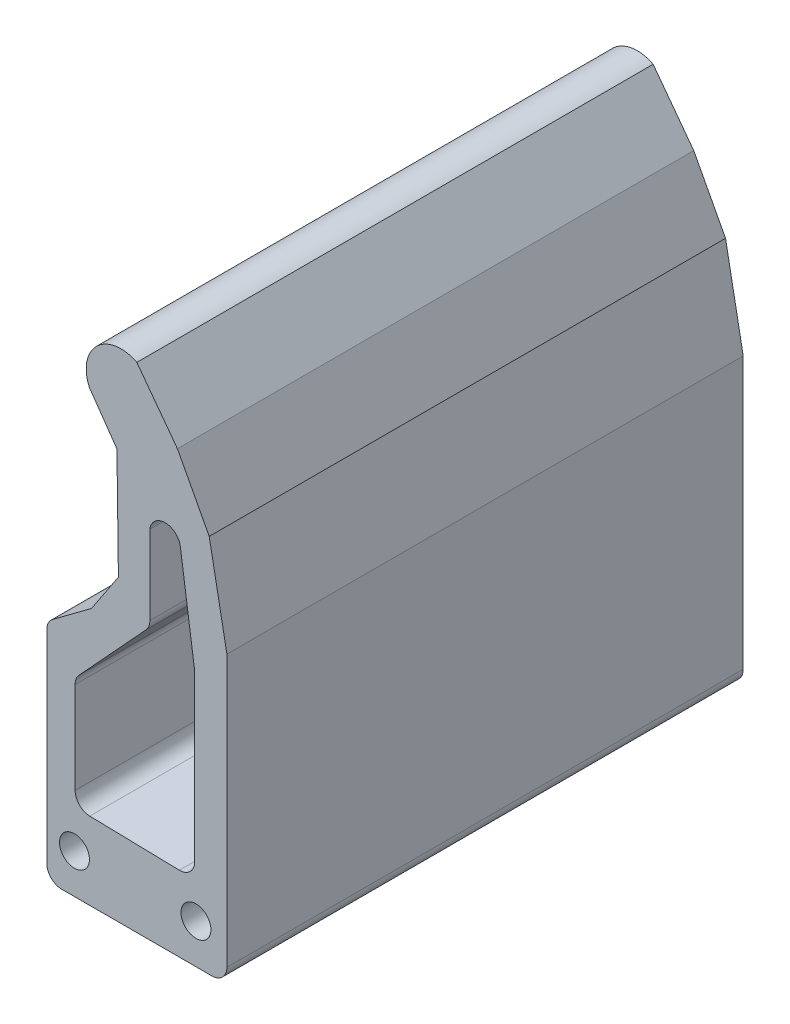
SolidWorks part; units mm, degrees
ref_plane "Front Plane" through (0, 0, 0) normal (0, 0, 1) x (1, 0, 0)
ref_plane "Top Plane" through (0, 0, 0) normal (0, 1, 0) x (1, 0, 0)
ref_plane "Right Plane" through (0, 0, 0) normal (1, 0, 0) x (0, 0, -1)
other "Graphic1"
ref_plane "Plane1" through (0, 0, 40) normal (0, 0, 1) x (1, 0, 0)
sketch "Sketch1" plane through (0, 0, 40) normal (0, 0, 1) x (1, 0, 0)
  line L0 (-312.0305, 377.8685) -> (-310.1939, 375.2448)
  line L1 (-310.1939, 375.2448) -> (-310.096, 367.8752)
  line L2 (-310.096, 367.8752) -> (-311.8891, 365.1664)
  line L3 (-311.8891, 365.1664) -> (-314.8817, 362.9367)
  line L4 (-314.8817, 362.9367) -> (-314.8817, 347.9184)
  line L5 (-314.8817, 347.9184) -> (-302.8474, 347.9184)
  line L6 (-302.8474, 347.9184) -> (-302.8474, 367.0456)
  line L7 (-302.8474, 367.0456) -> (-304.0281, 373.2638)
  line L8 (-304.0281, 373.2638) -> (-306.1533, 377.2782)
  line L9 (-306.1533, 377.2782) -> (-308.8645, 380.917)
  line L10 (-312.9884, 360.5984) -> (-312.9884, 353.11)
  line L11 (-312.9884, 353.11) -> (-305, 352.9273)
  line L12 (-305, 352.9273) -> (-305, 365)
  line L13 (-305, 365) -> (-305.9529, 371.67)
  line L14 (-312.9884, 360.5984) -> (-307.9946, 366.0233)
  line L15 (-307.9946, 366.0233) -> (-307.9946, 371.7027)
  arc A0 (-312.0305, 377.8685) -> (-308.8645, 380.917) centre (-309.9244, 378.8495) cw
  arc A1 (-307.9946, 371.7027) -> (-305.9529, 371.67) centre (-306.9758, 371.5556) cw
extrude "Boss-Extrude1" add sketch "Sketch1" along normal blind 34.5
fillet "Fillet1" radius 1 7 edges at (-314.8817, 347.9184, 57.25) (-305, 352.9273, 57.25) (-302.8474, 347.9184, 57.25) (-312.9884, 353.11, 57.25) (-314.8817, 362.9367, 57.25) (-312.9884, 360.5984, 57.25) (-307.9946, 366.0233, 57.25)
sketch "Sketch2" plane through (0, 0, 74.5) normal (0, 0, 1) x (1, 0, 0)
  circle A0 centre (-313.0311, 350.5603) radius 1
  circle A1 centre (-304.9145, 350.5603) radius 1
extrude "Cut-Extrude1" cut sketch "Sketch2" against normal through all
